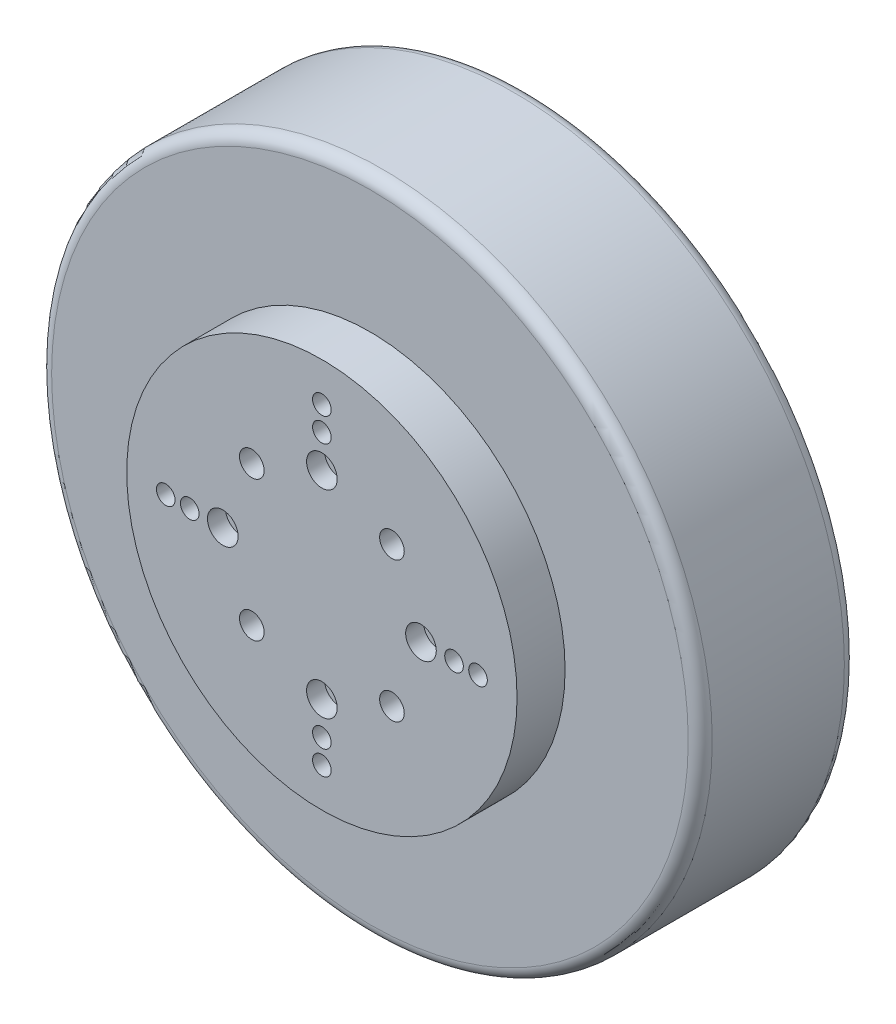
SolidWorks part; units mm, degrees
ref_plane "Front Plane" through (0, 0, 0) normal (0, 0, 1) x (1, 0, 0)
ref_plane "Top Plane" through (0, 0, 0) normal (0, 1, 0) x (1, 0, 0)
ref_plane "Right Plane" through (0, 0, 0) normal (1, 0, 0) x (0, 0, -1)
sketch "Sketch1" plane through (0, 0, 0) normal (0, 0, 1) x (1, 0, 0)
  line L0 (0, 0) -> (0, 21) construction
  circle A0 centre (0, 0) radius 55
  circle A1 centre (0, 0) radius 21 construction
  circle A2 centre (0, 21) radius 1.5
  circle A3 centre (14.8492, 14.8492) radius 1.5
  circle A4 centre (21, 0) radius 1.5
  circle A5 centre (14.8492, -14.8492) radius 1.5
  circle A6 centre (0, -21) radius 1.5
  circle A7 centre (-14.8492, -14.8492) radius 1.5
  circle A8 centre (-21, 0) radius 1.5
  circle A9 centre (-14.8492, 14.8492) radius 1.5
  dimension "D1" = 110
  dimension "D2" = 42
  dimension "D3" = 3
  dimension "D5" = 21
  dimension "D4" = 8
extrude "Boss-Extrude1" add sketch "Sketch1" along normal blind 26 contours A0
sketch "Sketch2" plane through (0, 0, 0) normal (0, 0, -1) x (-1, 0, 0)
  circle A1 centre (0, -21) radius 1.5
  circle A2 centre (0, -21) radius 1.5
  circle A3 centre (-14.8492, -14.8492) radius 1.5
  circle A4 centre (-14.8492, -14.8492) radius 1.5
  circle A5 centre (-21, 0) radius 1.5
  circle A6 centre (-21, 0) radius 1.5
  circle A7 centre (-14.8492, 14.8492) radius 1.5
  circle A8 centre (-14.8492, 14.8492) radius 1.5
  circle A9 centre (0, 21) radius 1.5
  circle A10 centre (0, 21) radius 1.5
  circle A13 centre (14.8492, 14.8492) radius 1.5
  circle A14 centre (14.8492, 14.8492) radius 1.5
  circle A15 centre (21, 0) radius 1.5
  circle A16 centre (21, 0) radius 1.5
  circle A17 centre (14.8492, -14.8492) radius 1.5
  circle A18 centre (14.8492, -14.8492) radius 1.5
  dimension "D1" = 0
  dimension "D2" = 0
  dimension "D3" = 0
  dimension "D4" = 0
  dimension "D5" = 0
  dimension "D7" = 0
  dimension "D8" = 0
  dimension "D9" = 0
extrude "Cut-Extrude1" cut sketch "Sketch2" against normal blind 3
sketch "Sketch3" plane through (0, 0, 26) normal (0, 0, 1) x (1, 0, 0)
  line L0 (0, 0) -> (0, 16.5) construction
  line L1 (0, 0) -> (-59.5603, 59.5603) construction
  line L2 (0, 0) -> (-87.189, 0) construction
  line L3 (0, 0) -> (-11.6673, 11.6673) construction
  line L4 (0, 0) -> (0, 22) construction
  circle A0 centre (0, 0) radius 26 construction
  circle A1 centre (0, 0) radius 22 construction
  circle A2 centre (0, 0) radius 16.5 construction
  circle A3 centre (0, 16.5) radius 2.55
  circle A4 centre (16.5, 0) radius 2.55
  circle A5 centre (0, -16.5) radius 2.55
  circle A6 centre (-16.5, 0) radius 2.55
  circle A7 centre (-11.6673, 11.6673) radius 2.05
  circle A8 centre (11.6673, 11.6673) radius 2.05
  circle A9 centre (11.6673, -11.6673) radius 2.05
  circle A10 centre (-11.6673, -11.6673) radius 2.05
  circle A11 centre (0, 22) radius 1.55
  circle A12 centre (0, 26) radius 1.55
  circle A13 centre (26, 0) radius 1.55
  circle A14 centre (22, 0) radius 1.55
  circle A15 centre (0, -26) radius 1.55
  circle A16 centre (0, -22) radius 1.55
  circle A17 centre (-26, 0) radius 1.55
  circle A18 centre (-22, 0) radius 1.55
  circle A19 centre (0, 0) radius 32.5
  dimension "D1" = 52
  dimension "D2" = 44
  dimension "D3" = 33
  dimension "D4" = 5.1
  dimension "D8" = 4.1
  dimension "D11" = 3.1
  dimension "D12" = 3.1
  dimension "D15" = 65
  dimension "D6" = 16.5
  dimension "D7" = 45
  dimension "D10" = 16.5
  dimension "D14" = 22
  dimension "D5" = 4
  dimension "D9" = 4
  dimension "D13" = 4
extrude "Boss-Extrude2" add sketch "Sketch3" along normal blind 8 contours A19
sketch "Sketch4" plane through (0, 0, 34) normal (0, 0, 1) x (1, 0, 0)
  circle A1 centre (-16.5, 0) radius 2.55
  circle A2 centre (-16.5, 0) radius 2.55
  circle A3 centre (0, -16.5) radius 2.55
  circle A4 centre (0, -16.5) radius 2.55
  circle A5 centre (16.5, 0) radius 2.55
  circle A6 centre (16.5, 0) radius 2.55
  circle A7 centre (0, 16.5) radius 2.55
  circle A8 centre (0, 16.5) radius 2.55
  circle A9 centre (0, 26) radius 1.55
  circle A10 centre (0, 26) radius 1.55
  circle A11 centre (0, 22) radius 1.55
  circle A12 centre (0, 22) radius 1.55
  circle A13 centre (-11.6673, -11.6673) radius 2.05
  circle A14 centre (-11.6673, -11.6673) radius 2.05
  circle A15 centre (11.6673, -11.6673) radius 2.05
  circle A16 centre (11.6673, -11.6673) radius 2.05
  circle A17 centre (11.6673, 11.6673) radius 2.05
  circle A18 centre (11.6673, 11.6673) radius 2.05
  circle A19 centre (-11.6673, 11.6673) radius 2.05
  circle A20 centre (-11.6673, 11.6673) radius 2.05
  circle A23 centre (-22, 0) radius 1.55
  circle A24 centre (-22, 0) radius 1.55
  circle A25 centre (-26, 0) radius 1.55
  circle A26 centre (-26, 0) radius 1.55
  circle A27 centre (0, -22) radius 1.55
  circle A28 centre (0, -22) radius 1.55
  circle A29 centre (0, -26) radius 1.55
  circle A30 centre (0, -26) radius 1.55
  circle A31 centre (22, 0) radius 1.55
  circle A32 centre (22, 0) radius 1.55
  circle A33 centre (26, 0) radius 1.55
  circle A34 centre (26, 0) radius 1.55
  dimension "D1" = 0
  dimension "D2" = 0
  dimension "D3" = 0
  dimension "D4" = 0
  dimension "D5" = 0
  dimension "D6" = 0
  dimension "D7" = 0
  dimension "D8" = 0
  dimension "D9" = 0
  dimension "D10" = 0
  dimension "D12" = 0
  dimension "D13" = 0
  dimension "D14" = 0
  dimension "D15" = 0
  dimension "D16" = 0
  dimension "D17" = 0
extrude "Cut-Extrude2" cut sketch "Sketch4" against normal blind 3
fillet "Fillet1" radius 2 2 edges at (55, 0, 26) (55, 0, 0)
sketch "Sketch5" plane through (0, 0, 0) normal (0, 0, -1) x (-1, 0, 0)
  line L0 (0, 53) -> (0, -53) construction
  circle A0 centre (0, 0) radius 53 construction
ref_plane "Plane1" through (0, 55, 0) normal (0, 1, 0) x (1, 0, 0)
sketch "Sketch6" plane through (0, 55, 0) normal (0, 1, 0) x (1, 0, 0)
  line L0 (0, -2) -> (0, -24) construction
  line L1 (55, -2) -> (-55, -2) construction
  line L2 (55, -24) -> (-55, -24) construction
sketch "Sketch7" plane through (0, 0, 0) normal (0, 1, 0) x (1, 0, 0)
  line L0 (0, 0) -> (0, -24) construction
  line L1 (55, -24) -> (-55, -24) construction
sketch "Sketch8" plane through (0, 0, 34) normal (0, 0, 1) x (1, 0, 0)
  line L0 (0, 0) -> (37.4767, 37.4767) construction
  line L1 (0, 0) -> (53, 0) construction
  circle A0 centre (0, 0) radius 53 construction
  dimension "D1" = 45
sketch "Sketch9" plane through (0, 0, 0) normal (0, 0, -1) x (-1, 0, 0)
  circle A0 centre (0, 0) radius 35 construction
  dimension "D1" = 70
